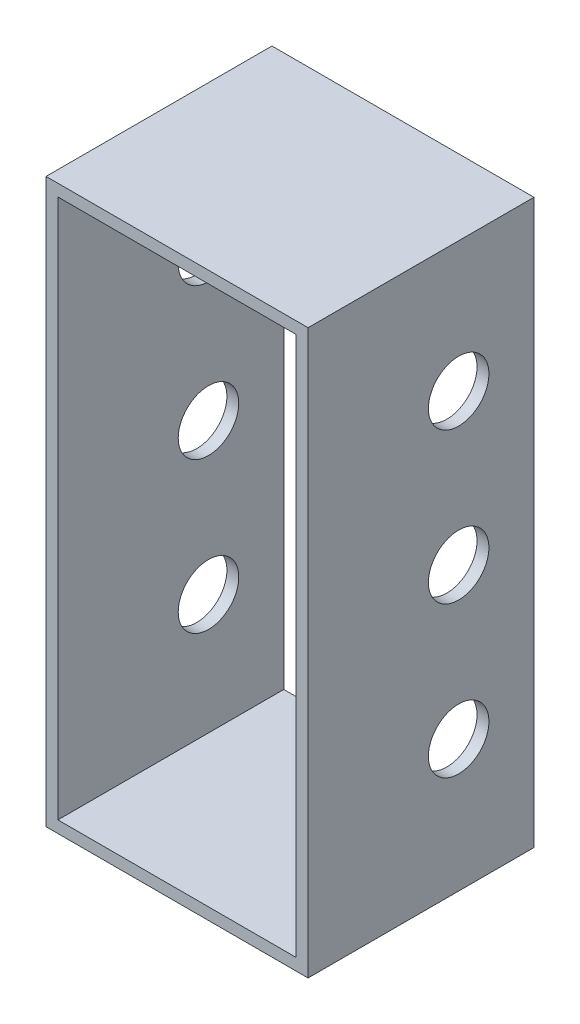
SolidWorks part; units mm, degrees
material "Nylon 101"
ref_plane "Front Plane" through (0, 0, 0) normal (0, 0, 1) x (1, 0, 0)
ref_plane "Top Plane" through (0, 0, 0) normal (0, 1, 0) x (1, 0, 0)
ref_plane "Right Plane" through (0, 0, 0) normal (1, 0, 0) x (0, 0, -1)
sketch "Sketch1" plane through (0, 0, 0) normal (0, 1, 0) x (1, 0, 0)
  line L1 (0, 0) -> (22.098, 0)
  line L2 (0, 0) -> (0, 19.05)
  line L3 (0, 19.05) -> (22.098, 19.05)
  line L4 (22.098, 0) -> (22.098, 19.05)
  dimension "D1" = 22.098
  dimension "D2" = 19.05
extrude "Boss-Extrude1" add sketch "Sketch1" along normal mid plane 47.498
sketch "Sketch2" plane through (0, 0, 0) normal (-1, 0, 0) x (0, 0, 1)
  line L0 (-12.7, -23.749) -> (-12.7, 23.749) construction
  line L1 (-19.05, -23.749) -> (0, -23.749) construction
  line L2 (-19.05, 23.749) -> (0, 23.749) construction
  line L3 (0, 23.749) -> (0, -23.749) construction
  circle A0 centre (-12.7, 12.7635) radius 2.5527
  circle A1 centre (-12.7, -12.6365) radius 2.5527
  circle A2 centre (-12.7, 0.0635) radius 2.5527
  dimension "D2" = 5.1054
  dimension "D1" = 12.7
  dimension "D3" = 11.1125
  dimension "D4" = 12.7
  dimension "D5" = 12.7
extrude "Cut-Extrude1" cut sketch "Sketch2" against normal through all
shell "Shell1" thickness 1
equation "\"D1@Shell1\"=1mm"
